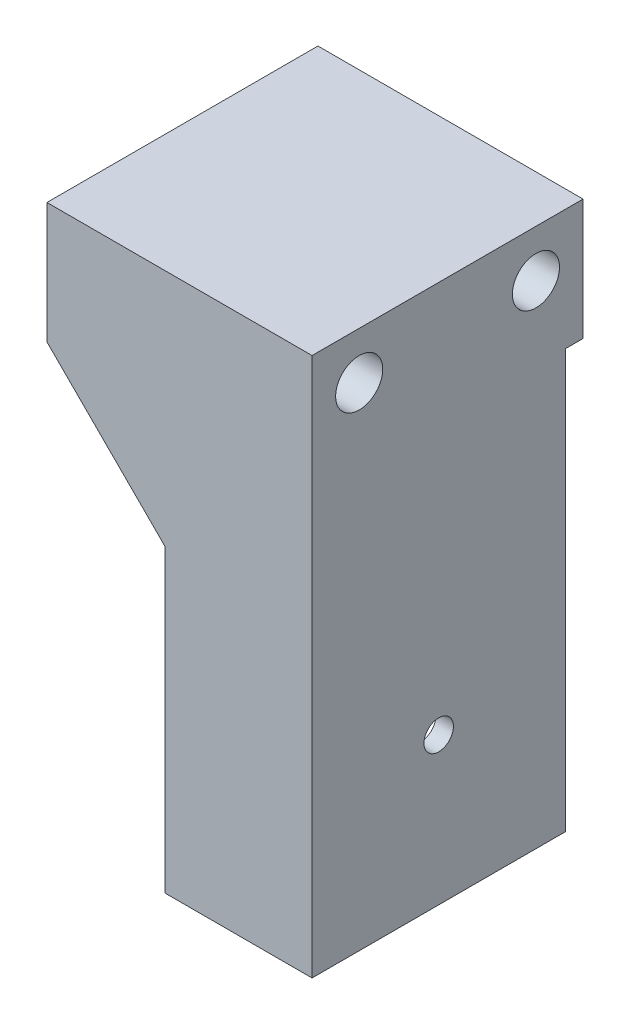
SolidWorks part; units mm, degrees
ref_plane "Front Plane" through (0, 0, 0) normal (0, 0, 1) x (1, 0, 0)
ref_plane "Top Plane" through (0, 0, 0) normal (0, 1, 0) x (1, 0, 0)
ref_plane "Right Plane" through (0, 0, 0) normal (1, 0, 0) x (0, 0, -1)
sketch "Sketch1" plane through (0, 0, 0) normal (0, 1, 0) x (1, 0, 0)
  line L0 (0, 0) -> (0, 40)
  line L1 (0, 40) -> (3, 40)
  line L2 (3, 40) -> (3, -3)
  line L3 (3, -3) -> (-22, -3)
  line L4 (-22, -3) -> (-22, 0)
  line L5 (-22, 0) -> (0, 0)
  dimension "D1" = 22
  dimension "D2" = 40
  dimension "D3" = 3
  dimension "D4" = 3
extrude "Boss-Extrude1" add sketch "Sketch1" along normal blind 75
sketch "Sketch2" plane through (0, 75, 0) normal (0, 1, 0) x (1, 0, 0)
  line L1 (0, 0) -> (-42, 0)
  line L2 (0, 0) -> (0, 40)
  line L3 (0, 40) -> (-42, 40)
  line L4 (-42, 0) -> (-42, 40)
  circle A0 centre (-17, 20) radius 2.5
  dimension "D3" = 5
  dimension "D1" = 42
  dimension "D2" = 17
extrude "Boss-Extrude2" add sketch "Sketch2" against normal blind 4
sketch "Sketch3" plane through (0, 0, 0) normal (0, 0, 1) x (1, 0, 0)
  line L0 (-22, 75) -> (-42, 75)
  line L1 (-42, 75) -> (-42, 71)
  line L2 (-42, 71) -> (-22, 51)
  line L3 (-22, 71) -> (-22, 0) construction
  line L4 (-22, 51) -> (-22, 75)
  dimension "D1" = 24
extrude "Boss-Extrude3" add sketch "Sketch3" along normal blind 3
sketch "Sketch4" plane through (3, 0, 0) normal (1, 0, 0) x (0, 0, -1)
  line L0 (-3, 75) -> (40, 75) construction
  circle A0 centre (18.5, 25) radius 2.5
  dimension "D1" = 5
  dimension "D2" = 50
extrude "Cut-Extrude1" cut sketch "Sketch4" against normal blind 3
sketch "Sketch5" plane through (-42, 0, 0) normal (-1, 0, 0) x (0, 0, 1)
  line L0 (-35, 83.5) -> (-5, 83.5) construction
  line L1 (-20, 83.5) -> (-20, 71) construction
  line L3 (-40, 75) -> (-40, 91.5)
  line L4 (-40, 91.5) -> (3, 91.5)
  line L5 (3, 91.5) -> (3, 75)
  line L6 (3, 75) -> (-40, 75)
  line L7 (-40, 71) -> (0, 71) construction
  circle A0 centre (-35, 83.5) radius 4
  circle A1 centre (-5, 83.5) radius 4
  dimension "D2" = 8
  dimension "D3" = 12.5
  dimension "D1" = 30
  dimension "D4" = 8
extrude "Boss-Extrude4" add sketch "Sketch5" against normal up to surface (45 mm away) up to face at (3, 25, -21)
sketch "Sketch6" plane through (0, 0, -40) normal (0, 0, -1) x (-1, 0, 0)
  line L0 (-3, 91.5) -> (-3, 71)
  line L1 (-3, 91.5) -> (-3, 0) construction
  line L2 (-3, 71) -> (42, 71)
  line L4 (42, 71) -> (42, 91.5)
  line L5 (42, 91.5) -> (-3, 91.5)
extrude "Boss-Extrude6" add sketch "Sketch6" along normal blind 3
